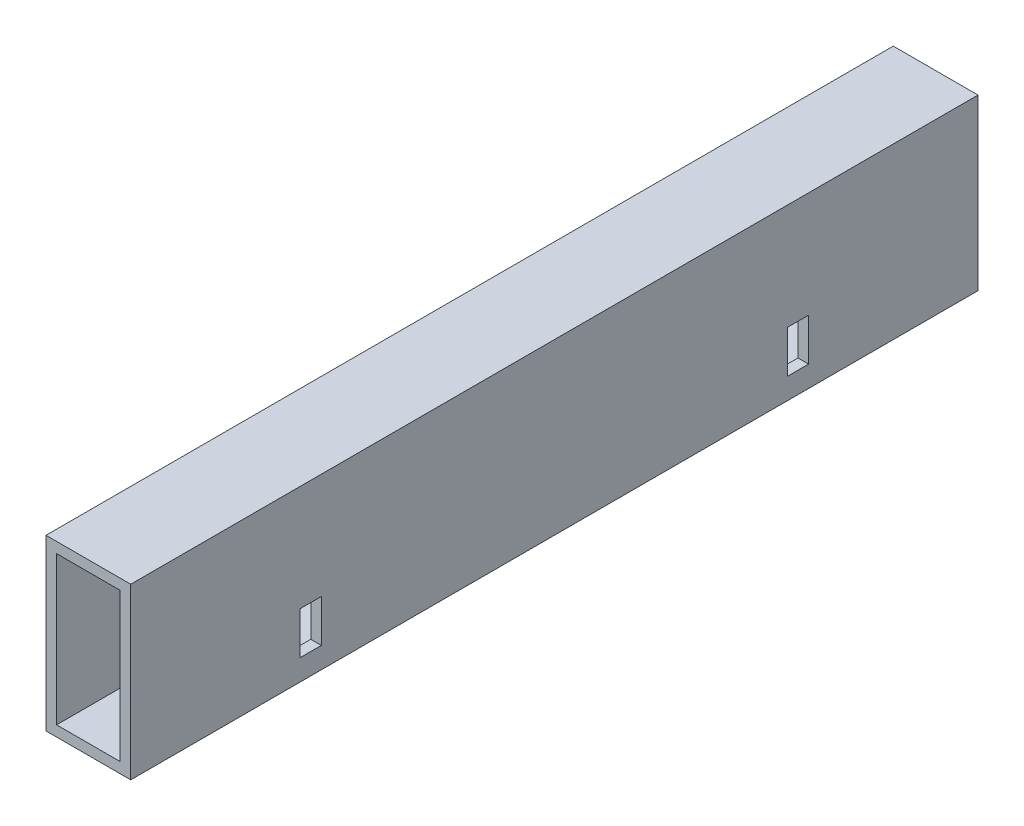
SolidWorks part; units mm, degrees
ref_plane "Front Plane" through (0, 0, 0) normal (0, 0, 1) x (1, 0, 0)
ref_plane "Top Plane" through (0, 0, 0) normal (0, 1, 0) x (1, 0, 0)
ref_plane "Right Plane" through (0, 0, 0) normal (1, 0, 0) x (0, 0, -1)
sketch "Sketch1" plane through (0, 0, 0) normal (0, 0, 1) x (1, 0, 0)
  line L0 (22.225, 3.175) -> (22.225, 47.625)
  line L1 (0, 0) -> (25.4, 0)
  line L2 (0, 0) -> (0, 50.8)
  line L3 (0, 50.8) -> (25.4, 50.8)
  line L4 (25.4, 0) -> (25.4, 50.8)
  line L5 (3.175, 47.625) -> (22.225, 47.625)
  line L6 (3.175, 3.175) -> (3.175, 47.625)
  line L7 (3.175, 3.175) -> (22.225, 3.175)
  dimension "D1" = 25.4
  dimension "D2" = 50.8
  dimension "D3" = 3.175
extrude "Boss-Extrude1" add sketch "Sketch1" along normal blind 254
sketch "Sketch2" plane through (25.4, 0, 0) normal (1, 0, 0) x (0, 0, -1)
  line L0 (-127, 50.8) -> (-127, 0) construction
  line L1 (-254, 50.8) -> (0, 50.8) construction
  line L2 (-254, 0) -> (0, 0) construction
  line L3 (-254, 0) -> (-254, 50.8) construction
  circle A0 centre (-209.55, 12.7) radius 6.4822
  circle A1 centre (-44.45, 12.7) radius 6.4822
  dimension "D1" = 44.45
  dimension "D2" = 12.7
extrude "Cut-Extrude1" cut sketch "Sketch2" against normal blind 254
sketch "Sketch3" plane through (0, 0, 0) normal (-1, 0, 0) x (0, 0, 1)
  circle A0 centre (209.55, 12.7) radius 6.4822
  circle A1 centre (44.45, 12.7) radius 6.4822
extrude "Boss-Extrude2" add sketch "Sketch3" against normal blind 25.4
sketch "Sketch4" plane through (0, 0, 254) normal (0, 0, 1) x (1, 0, 0)
  line L1 (22.225, 3.175) -> (3.175, 3.175)
  line L2 (22.225, 3.175) -> (22.225, 47.625)
  line L3 (22.225, 47.625) -> (3.175, 47.625)
  line L4 (3.175, 3.175) -> (3.175, 47.625)
extrude "Cut-Extrude2" cut sketch "Sketch4" against normal blind 254
sketch "Sketch5" plane through (0, 0, 0) normal (-1, 0, 0) x (0, 0, 1)
  line L0 (127, 50.8) -> (127, 0) construction
  line L1 (196.85, 19.05) -> (196.85, 6.3267)
  line L2 (196.85, 6.3267) -> (203.2, 6.35)
  line L3 (203.2, 6.35) -> (203.2, 19.05)
  line L4 (203.2, 19.05) -> (196.85, 19.05)
  line L5 (254, 50.8) -> (0, 50.8) construction
  line L6 (254, 0) -> (0, 0) construction
  line L7 (57.15, 6.3267) -> (50.8, 6.35)
  line L8 (50.8, 6.35) -> (50.8, 19.05)
  line L9 (50.8, 19.05) -> (57.15, 19.05)
  line L10 (57.15, 19.05) -> (57.15, 6.3267)
  dimension "D1" = 12.7
  dimension "D2" = 6.35
extrude "Cut-Extrude3" cut sketch "Sketch5" against normal blind 254
